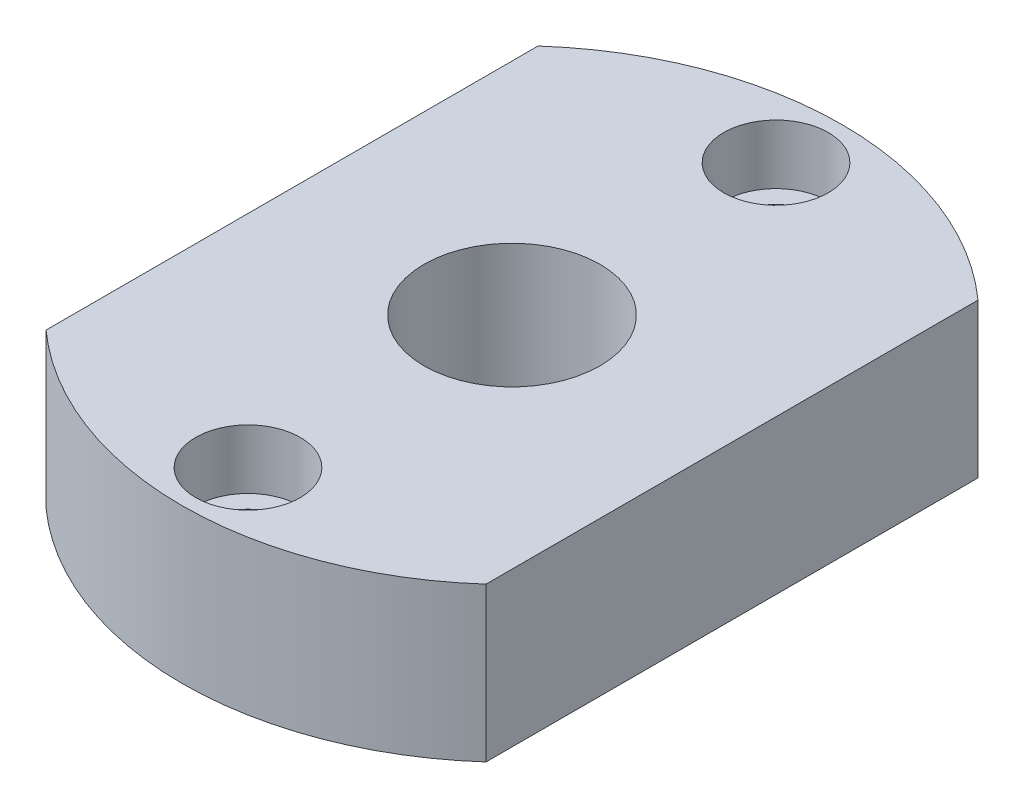
SolidWorks part; units mm, degrees
ref_plane "前视基准面" through (0, 0, 0) normal (0, 0, 1) x (1, 0, 0)
ref_plane "上视基准面" through (0, 0, 0) normal (0, 1, 0) x (1, 0, 0)
ref_plane "右视基准面" through (0, 0, 0) normal (1, 0, 0) x (0, 0, -1)
other "Configuration Table"
sketch "草图1" plane through (0, 0, 0) normal (0, 1, 0) x (1, 0, 0)
  circle A0 centre (0, 0) radius 30
  dimension "D1" = 60
extrude "凸台-拉伸1" add sketch "草图1" along normal blind 14
sketch "草图2" plane through (0, 14, 0) normal (0, 1, 0) x (1, 0, 0)
  circle A0 centre (0, 0) radius 8
  dimension "D1" = 16
extrude "切除-拉伸1" cut sketch "草图2" against normal blind 14
sketch "草图3" plane through (0, 14, 0) normal (0, 1, 0) x (1, 0, 0)
  line L0 (30, 0) -> (-30, 0) construction
  circle A0 centre (0, 24) radius 3
  circle A1 centre (0, 0) radius 30 construction
  circle A2 centre (0, -24) radius 3
  point P7 (0, 0)
  dimension "D1" = 6
  dimension "D2" = 24
extrude "切除-拉伸2" cut sketch "草图3" against normal blind 14
sketch "草图4" plane through (0, 14, 0) normal (0, 1, 0) x (1, 0, 0)
  circle A0 centre (0, 24) radius 4.75
  circle A1 centre (0, -24) radius 4.75
  dimension "D1" = 9.5
  dimension "D2" = 9.5
extrude "切除-拉伸3" cut sketch "草图4" against normal blind 5.4
sketch "草图5" plane through (0, 14, 0) normal (0, 1, 0) x (1, 0, 0)
  line L1 (-20, -32.5) -> (20, -32.5)
  line L2 (-20, -32.5) -> (-20, 32.5)
  line L3 (-20, 32.5) -> (20, 32.5)
  line L4 (20, -32.5) -> (20, 32.5)
  line L5 (-20, -32.5) -> (20, 32.5) construction
  line L6 (-20, 32.5) -> (20, -32.5) construction
  point P0 (0, 0)
  dimension "D1" = 40
  dimension "D2" = 65
extrude "切除-拉伸4" cut sketch "草图5" against normal blind 14 flip side to cut
